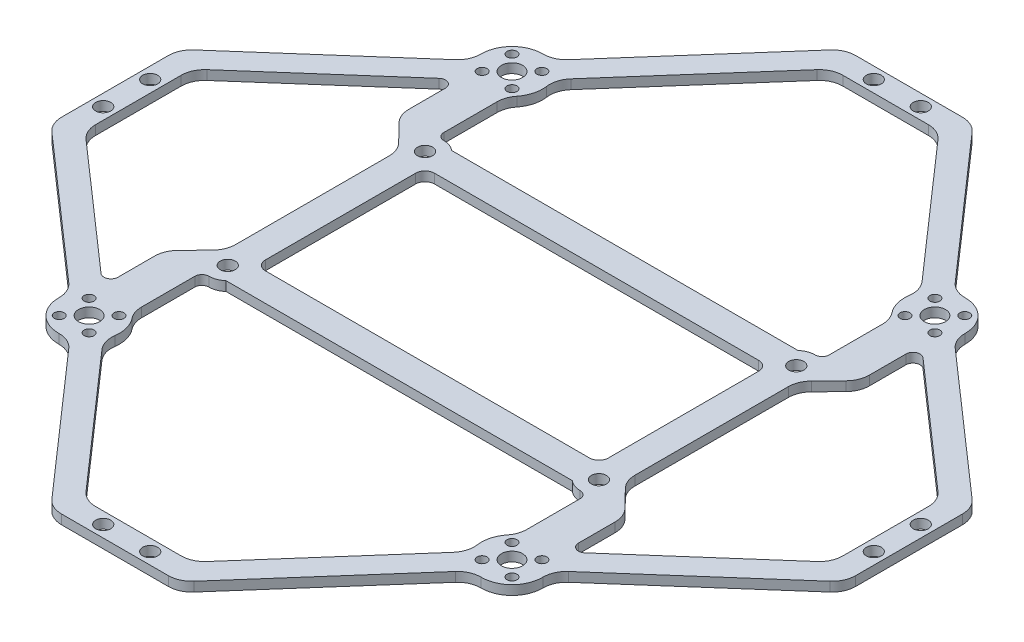
SolidWorks part; units mm, degrees
ref_plane "前视基准面" through (0, 0, 0) normal (0, 0, 1) x (1, 0, 0)
ref_plane "上视基准面" through (0, 0, 0) normal (0, 1, 0) x (1, 0, 0)
ref_plane "右视基准面" through (0, 0, 0) normal (1, 0, 0) x (0, 0, -1)
other "Configuration Table"
sketch "草图1" plane through (0, 0, 0) normal (0, 1, 0) x (1, 0, 0)
  line L0 (49, -45) -> (49, -39.8765) construction
  line L1 (-45, -45) -> (45, -45) construction
  line L2 (-45, -45) -> (-45, 45) construction
  line L3 (-45, 45) -> (45, 45) construction
  line L4 (45, -45) -> (45, 45) construction
  line L5 (-45, -45) -> (45, 45) construction
  line L6 (-45, 45) -> (45, -45) construction
  line L7 (-43.5, -25) -> (43.5, -25) construction
  line L8 (-43.5, -25) -> (-43.5, 25) construction
  line L9 (-43.5, 25) -> (43.5, 25) construction
  line L10 (43.5, -25) -> (43.5, 25) construction
  line L11 (-43.5, -25) -> (43.5, 25) construction
  line L12 (-43.5, 25) -> (43.5, -25) construction
  line L13 (-10, -10) -> (10, -10) construction
  line L14 (-10, -10) -> (-10, 10) construction
  line L15 (-10, 10) -> (10, 10) construction
  line L16 (10, -10) -> (10, 10) construction
  line L17 (-10, -10) -> (10, 10) construction
  line L18 (-10, 10) -> (10, -10) construction
  line L19 (41, -45) -> (41, 45) construction
  line L20 (41, 37.8411) -> (41, 26.5)
  line L21 (43.9235, 19.8039) -> (47.5765, 23.5429)
  line L22 (49, 34.8449) -> (49, 27.037)
  line L23 (0, 0) -> (14.7512, 0) construction
  line L24 (41, -26.5) -> (41, -37.8411)
  line L25 (49, -34.8449) -> (49, -27.037)
  line L26 (47.5765, -23.5429) -> (43.9235, -19.8039)
  line L27 (0, 0) -> (0, 21.9355) construction
  line L28 (-49, -45) -> (-49, -39.8765) construction
  line L29 (-41, -45) -> (-41, 45) construction
  line L30 (-45, -45) -> (-45, 45) construction
  line L31 (-41, -26.5) -> (-41, -37.8411)
  line L32 (-49, -34.8449) -> (-49, -27.037)
  line L33 (-47.5765, -23.5429) -> (-43.9235, -19.8039)
  line L34 (-49, 34.8449) -> (-49, 27.037)
  line L35 (-47.5765, 23.5429) -> (-43.9235, 19.8039)
  line L36 (-41, 37.8411) -> (-41, 26.5)
  line L37 (-39.5, 21) -> (39.5, 21) construction
  line L38 (39.5, 21) -> (39.5, -21) construction
  line L39 (-39.5, 21) -> (-39.5, -21) construction
  line L40 (-39.5, -21) -> (39.5, -21) construction
  line L42 (42.5, 16.3098) -> (42.5, -16.3098)
  line L44 (-42.5, 16.3098) -> (-42.5, -16.3098)
  line L45 (-34.5, -18) -> (34.5, -18)
  line L46 (36.5, 16) -> (36.5, -16)
  line L47 (-34.5, 18) -> (34.5, 18)
  line L48 (-36.5, 16) -> (-36.5, -16)
  line L49 (-42.5, 24) -> (-42.5, -24) construction
  line L50 (-36.8542, 24) -> (36.8542, 24)
  line L51 (-42.5, 24) -> (42.5, 24) construction
  line L52 (42.5, 24) -> (42.5, -24) construction
  line L53 (-36.8542, -24) -> (36.8542, -24)
  line L54 (-42.5, -24) -> (42.5, -24) construction
  line L55 (-45, 45) -> (-12.5, 82) construction
  line L56 (-12.5, 82) -> (12.5, 82) construction
  line L57 (12.5, 82) -> (45, 45) construction
  line L58 (-37.3685, 49.9) -> (-12.862, 77.7997)
  line L59 (-9.1054, 79.5) -> (9.1054, 79.5)
  line L60 (12.862, 77.7997) -> (37.3685, 49.9)
  line L61 (-41.1251, 53.1997) -> (-15.125, 82.7997)
  line L62 (-11.3685, 84.5) -> (11.3685, 84.5)
  line L63 (15.125, 82.7997) -> (41.1251, 53.1997)
  line L64 (82, 12.5) -> (82, -12.5) construction
  line L65 (45, 45) -> (82, 12.5) construction
  line L66 (82, -12.5) -> (45, -45) construction
  line L67 (12.5, -82) -> (-12.5, -82) construction
  line L68 (45, -45) -> (12.5, -82) construction
  line L69 (-12.5, -82) -> (-45, -45) construction
  line L70 (-82, -12.5) -> (-82, 12.5) construction
  line L71 (-45, -45) -> (-82, -12.5) construction
  line L72 (-82, 12.5) -> (-45, 45) construction
  line L73 (-46.8783, 46.6499) -> (-13.6315, 84.5) construction
  line L74 (-43.1217, 43.3501) -> (-11.3685, 79.5) construction
  line L75 (11.3685, 79.5) -> (43.1217, 43.3501) construction
  line L76 (-13.6315, -84.5) -> (-46.8783, -46.6499) construction
  line L77 (13.6315, 84.5) -> (46.8783, 46.6499) construction
  line L78 (-79.5, -9.1054) -> (-79.5, 9.1054)
  line L79 (-77.7997, 12.862) -> (-51.4899, 35.9719)
  line L80 (84.5, -13.6315) -> (46.6499, -46.8783) construction
  line L81 (9.1054, -79.5) -> (-9.1054, -79.5)
  line L82 (-12.862, -77.7997) -> (-37.3685, -49.9)
  line L83 (51.4899, 35.9719) -> (77.7997, 12.862)
  line L84 (79.5, 9.1054) -> (79.5, -9.1054)
  line L85 (77.7997, -12.862) -> (51.4899, -35.9719)
  line L86 (-49, -38.159) -> (-49, 38.159) construction
  line L87 (-84.5, -11.3685) -> (-84.5, 11.3685)
  line L88 (-82.7997, 15.125) -> (-53.1997, 41.1251)
  line L89 (79.5, -11.3685) -> (43.3501, -43.1217) construction
  line L90 (11.3685, -84.5) -> (-11.3685, -84.5)
  line L91 (-15.125, -82.7997) -> (-41.1251, -53.1997)
  line L92 (43.3501, 43.1217) -> (79.5, 11.3685) construction
  line L93 (84.5, 11.3685) -> (84.5, -11.3685)
  line L94 (82.7997, -15.125) -> (53.1997, -41.1251)
  line L95 (-53.1997, -41.1251) -> (-82.7997, -15.125)
  line L96 (-84.5, 13.6315) -> (-46.6499, 46.8783) construction
  line L97 (-79.5, 11.3685) -> (-43.3501, 43.1217) construction
  line L98 (-46.6499, -46.8783) -> (-84.5, -13.6315) construction
  line L99 (-51.4899, -35.9719) -> (-77.7997, -12.862)
  line L100 (-43.3501, -43.1217) -> (-79.5, -11.3685) construction
  line L101 (-11.3685, -79.5) -> (-43.1217, -43.3501) construction
  line L102 (-49, 41.4865) -> (-49, 45) construction
  line L103 (37.3685, -49.9) -> (12.862, -77.7997)
  line L104 (43.1217, -43.3501) -> (11.3685, -79.5) construction
  line L105 (46.8783, -46.6499) -> (13.6315, -84.5) construction
  line L106 (41.1251, -53.1997) -> (15.125, -82.7997)
  line L107 (49, -38.159) -> (49, 38.159) construction
  line L108 (49, -45) -> (49, 45) construction
  line L109 (49, 39.8765) -> (49, 45) construction
  line L110 (53.1997, 41.1251) -> (82.7997, 15.125)
  line L111 (46.6499, 46.8783) -> (84.5, 13.6315) construction
  line L112 (79.5, 11.3685) -> (79.5, -11.3685) construction
  line L113 (84.5, 13.6315) -> (84.5, -13.6315) construction
  line L114 (13.6315, -84.5) -> (-13.6315, -84.5) construction
  line L115 (11.3685, -79.5) -> (-11.3685, -79.5) construction
  line L116 (-79.5, -11.3685) -> (-79.5, 11.3685) construction
  line L117 (-84.5, -13.6315) -> (-84.5, 13.6315) construction
  line L118 (-13.6315, 84.5) -> (13.6315, 84.5) construction
  line L119 (-11.3685, 79.5) -> (11.3685, 79.5) construction
  line L120 (36.5, 18) -> (36.5, -18) construction
  line L121 (-36.5, 18) -> (36.5, 18) construction
  line L122 (-36.5, -18) -> (36.5, -18) construction
  line L123 (-36.5, 18) -> (-36.5, -18) construction
  circle A0 centre (45, 45) radius 31.5 construction
  circle A1 centre (-45, 45) radius 31.5 construction
  circle A2 centre (-45, -45) radius 31.5 construction
  circle A3 centre (45, -45) radius 31.5 construction
  circle A4 centre (-45, 45) radius 9.5 construction
  circle A5 centre (45, 45) radius 9.5 construction
  circle A6 centre (45, -45) radius 9.5 construction
  circle A7 centre (-45, -45) radius 9.5 construction
  circle A8 centre (-39.5, 21) radius 1.6
  circle A9 centre (39.5, 21) radius 1.6
  circle A10 centre (39.5, -21) radius 1.6
  circle A11 centre (-39.5, -21) radius 1.6
  circle A12 centre (-10, 10) radius 1.6 construction
  circle A13 centre (10, 10) radius 1.6 construction
  circle A14 centre (-10, -10) radius 1.6 construction
  circle A15 centre (10, -10) radius 1.6 construction
  arc A16 (51.4997, 44.9331) -> (44.9331, 51.4997) centre (45, 45) ccw
  arc A17 (-39.913, 40.9537) -> (-38.5632, 45.9045) centre (-45, 45) ccw
  arc A19 (39.913, -40.9537) -> (38.5632, -45.9045) centre (45, -45) ccw
  arc A20 (39.5, 25) -> (36.8542, 24) centre (39.5, 21) ccw
  arc A22 (41, 26.5) -> (39.5, 25) centre (39.5, 26.5) cw
  arc A23 (41, -26.5) -> (39.5, -25) centre (39.5, -26.5) ccw
  arc A24 (-36.8542, 24) -> (-39.5, 25) centre (-39.5, 21) ccw
  arc A25 (-39.5, -25) -> (-36.8542, -24) centre (-39.5, -21) ccw
  arc A26 (-41, -26.5) -> (-39.5, -25) centre (-39.5, -26.5) cw
  arc A27 (-41, 26.5) -> (-39.5, 25) centre (-39.5, 26.5) ccw
  arc A28 (-49, -27.037) -> (-47.5765, -23.5429) centre (-44, -27.037) cw
  arc A29 (36.8542, -24) -> (39.5, -25) centre (39.5, -21) ccw
  arc A30 (49, -27.037) -> (47.5765, -23.5429) centre (44, -27.037) ccw
  arc A31 (47.5765, 23.5429) -> (49, 27.037) centre (44, 27.037) ccw
  arc A32 (-49, 27.037) -> (-47.5765, 23.5429) centre (-44, 27.037) ccw
  arc A33 (43.9235, -19.8039) -> (42.5, -16.3098) centre (47.5, -16.3098) cw
  arc A34 (43.9235, 19.8039) -> (42.5, 16.3098) centre (47.5, 16.3098) ccw
  arc A35 (-42.5, -16.3098) -> (-43.9235, -19.8039) centre (-47.5, -16.3098) cw
  arc A36 (-42.5, 16.3098) -> (-43.9235, 19.8039) centre (-47.5, 16.3098) ccw
  circle A37 centre (45, 45) radius 2.25
  circle A38 centre (48.182, 48.182) radius 1.05
  arc A57 (-44.9331, 51.4997) -> (-51.4997, 44.9331) centre (-45, 45) ccw
  arc A58 (38.5632, 45.9045) -> (39.913, 40.9537) centre (45, 45) ccw
  arc A59 (-38.5632, -45.9045) -> (-39.913, -40.9537) centre (-45, -45) ccw
  arc A60 (-51.4997, -44.9331) -> (-44.9331, -51.4997) centre (-45, -45) ccw
  arc A61 (44.9331, -51.4997) -> (51.4997, -44.9331) centre (45, -45) ccw
  circle A62 centre (5, 82) radius 1.6
  circle A63 centre (-5, 82) radius 1.6
  circle A64 centre (82, 5) radius 1.6
  circle A65 centre (82, -5) radius 1.6
  circle A66 centre (5, -82) radius 1.6
  circle A67 centre (-5, -82) radius 1.6
  circle A68 centre (-82, -5) radius 1.6
  circle A69 centre (-82, 5) radius 1.6
  arc A70 (77.7997, 12.862) -> (79.5, 9.1054) centre (74.5, 9.1054) cw
  arc A71 (82.7997, 15.125) -> (84.5, 11.3685) centre (79.5, 11.3685) cw
  arc A72 (84.5, -11.3685) -> (82.7997, -15.125) centre (79.5, -11.3685) cw
  arc A73 (79.5, -9.1054) -> (77.7997, -12.862) centre (74.5, -9.1054) cw
  arc A74 (15.125, -82.7997) -> (11.3685, -84.5) centre (11.3685, -79.5) cw
  arc A75 (12.862, -77.7997) -> (9.1054, -79.5) centre (9.1054, -74.5) cw
  arc A76 (-11.3685, -84.5) -> (-15.125, -82.7997) centre (-11.3685, -79.5) cw
  arc A77 (-9.1054, -79.5) -> (-12.862, -77.7997) centre (-9.1054, -74.5) cw
  arc A78 (-77.7997, -12.862) -> (-79.5, -9.1054) centre (-74.5, -9.1054) cw
  arc A79 (-82.7997, -15.125) -> (-84.5, -11.3685) centre (-79.5, -11.3685) cw
  arc A80 (-79.5, 9.1054) -> (-77.7997, 12.862) centre (-74.5, 9.1054) cw
  arc A81 (-84.5, 11.3685) -> (-82.7997, 15.125) centre (-79.5, 11.3685) cw
  arc A82 (11.3685, 84.5) -> (15.125, 82.7997) centre (11.3685, 79.5) cw
  arc A83 (9.1054, 79.5) -> (12.862, 77.7997) centre (9.1054, 74.5) cw
  arc A84 (-12.862, 77.7997) -> (-9.1054, 79.5) centre (-9.1054, 74.5) cw
  arc A85 (-15.125, 82.7997) -> (-11.3685, 84.5) centre (-11.3685, 79.5) cw
  arc A86 (-53.1997, 41.1251) -> (-51.4997, 44.9331) centre (-56.4994, 44.8816) ccw
  arc A87 (-41.1251, 53.1997) -> (-44.9331, 51.4997) centre (-44.8816, 56.4994) cw
  arc A88 (41.1251, 53.1997) -> (44.9331, 51.4997) centre (44.8816, 56.4994) ccw
  arc A89 (51.4997, 44.9331) -> (53.1997, 41.1251) centre (56.4994, 44.8816) ccw
  arc A90 (53.1997, -41.1251) -> (51.4997, -44.9331) centre (56.4994, -44.8816) ccw
  arc A91 (44.9331, -51.4997) -> (41.1251, -53.1997) centre (44.8816, -56.4994) ccw
  arc A92 (-41.1251, -53.1997) -> (-44.9331, -51.4997) centre (-44.8816, -56.4994) ccw
  arc A93 (-53.1997, -41.1251) -> (-51.4997, -44.9331) centre (-56.4994, -44.8816) cw
  arc A94 (49, 34.8449) -> (51.4899, 35.9719) centre (50.5, 34.8449) cw
  arc A95 (51.4899, -35.9719) -> (49, -34.8449) centre (50.5, -34.8449) cw
  arc A96 (-51.4899, -35.9719) -> (-49, -34.8449) centre (-50.5, -34.8449) ccw
  arc A97 (-51.4899, 35.9719) -> (-49, 34.8449) centre (-50.5, 34.8449) cw
  arc A98 (36.5, 16) -> (34.5, 18) centre (34.5, 16) ccw
  arc A99 (34.5, -18) -> (36.5, -16) centre (34.5, -16) ccw
  arc A100 (-34.5, -18) -> (-36.5, -16) centre (-34.5, -16) cw
  arc A101 (-34.5, 18) -> (-36.5, 16) centre (-34.5, 16) ccw
  circle A102 centre (48.182, 41.818) radius 1.05
  circle A103 centre (41.818, 41.818) radius 1.05
  circle A104 centre (41.818, 48.182) radius 1.05
  circle A105 centre (48.182, -41.818) radius 1.05
  circle A106 centre (48.182, -48.182) radius 1.05
  circle A107 centre (45, -45) radius 2.25
  circle A108 centre (41.818, -41.818) radius 1.05
  circle A109 centre (41.818, -48.182) radius 1.05
  circle A110 centre (-41.818, -48.182) radius 1.05
  circle A111 centre (-48.182, -48.182) radius 1.05
  circle A112 centre (-45, -45) radius 2.25
  circle A113 centre (-41.818, -41.818) radius 1.05
  circle A114 centre (-48.182, -41.818) radius 1.05
  circle A115 centre (-48.182, 41.818) radius 1.05
  circle A116 centre (-48.182, 48.182) radius 1.05
  circle A117 centre (-45, 45) radius 2.25
  circle A118 centre (-41.818, 41.818) radius 1.05
  circle A119 centre (-41.818, 48.182) radius 1.05
  arc A120 (37.3685, 49.9) -> (38.5632, 45.9045) centre (33.6119, 46.6003) cw
  arc A121 (-37.3685, 49.9) -> (-38.5632, 45.9045) centre (-33.6119, 46.6003) ccw
  arc A122 (38.5632, -45.9045) -> (37.3685, -49.9) centre (33.6119, -46.6003) cw
  arc A123 (-37.3685, -49.9) -> (-38.5632, -45.9045) centre (-33.6119, -46.6003) cw
  arc A124 (39.913, 40.9537) -> (41, 37.8411) centre (36, 37.8411) cw
  arc A125 (-39.913, 40.9537) -> (-41, 37.8411) centre (-36, 37.8411) ccw
  arc A126 (39.913, -40.9537) -> (41, -37.8411) centre (36, -37.8411) ccw
  arc A127 (-39.913, -40.9537) -> (-41, -37.8411) centre (-36, -37.8411) cw
  point P0 (0, 0)
  point P19 (0, 0)
  point P32 (0, 0)
  point P94 (0, 0)
  point P101 (0, 0)
  point P104 (-49, -25)
  point P107 (49, -25)
  point P110 (49, 25)
  point P113 (-49, 25)
  point P114 (0, 0)
  point P125 (45, 45)
  point P129 (45, 45)
  point P130 (0, 0)
  point P156 (0, 0)
  point P178 (0, 0)
  point P220 (0, 23.5429)
  point P236 (0, 0)
  point P288 (-42.9186, 51.1578)
  point P328 (0, 0)
  point P331 (39.1621, 47.8581)
  point P340 (41, 39.8765)
  point P343 (-41, 39.8765)
  point P346 (41, -39.8765)
  point P349 (-41, -39.8765)
  dimension "D3" = 63
  dimension "D4" = 63
  dimension "D5" = 63
  dimension "D6" = 63
  dimension "D7" = 19
  dimension "D8" = 19
  dimension "D9" = 19
  dimension "D10" = 19
  dimension "D15" = 3.2
  dimension "D18" = 3.2
  dimension "D21" = 3.2
  dimension "D24" = 3.2
  dimension "D27" = 3.2
  dimension "D28" = 3.2
  dimension "D29" = 3.2
  dimension "D30" = 3.2
  dimension "D31" = 13
  dimension "D32" = 13
  dimension "D33" = 3.2
  dimension "D34" = 13
  dimension "D35" = 8
  dimension "D36" = 3
  dimension "D17" = 8
  dimension "D23" = 8
  dimension "D39" = 5
  dimension "D40" = 5
  dimension "D41" = 4.5
  dimension "D42" = 2.1
  dimension "D44" = 4
  dimension "D54" = 3.2
  dimension "D58" = 5
  dimension "D59" = 5
  dimension "D60" = 1.5
  dimension "D61" = 2
  dimension "D62" = 5
  dimension "D63" = 5
  dimension "D1" = 90
  dimension "D2" = 90
  dimension "D11" = 87
  dimension "D12" = 50
  dimension "D13" = 3
  dimension "D14" = 4
  dimension "D16" = 4
  dimension "D19" = 3
  dimension "D20" = 4
  dimension "D22" = 4
  dimension "D25" = 20
  dimension "D26" = 20
  dimension "D43" = 4.5
  dimension "D46" = 25
  dimension "D47" = 12.5
  dimension "D50" = 82
  dimension "D55" = 5
  dimension "D56" = 5
  dimension "D37" = 4
  dimension "D38" = 4
  dimension "D48" = 2.5
  dimension "D49" = 2.5
  dimension "D52" = 2.5
  dimension "D53" = 2.5
  dimension "D51" = 4
  dimension "D57" = 4
  dimension "D45" = 4
extrude "凸台-拉伸2" add sketch "草图1" along normal blind 2
